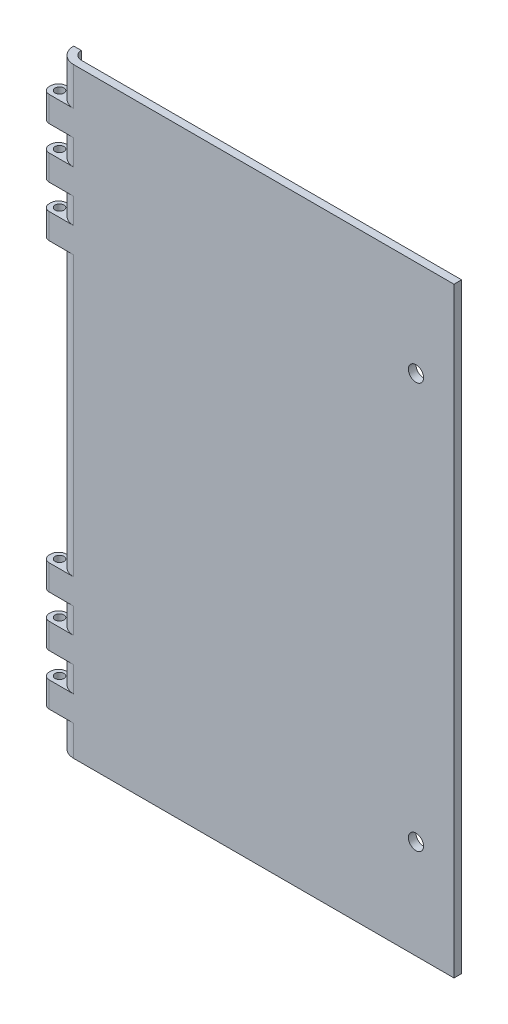
SolidWorks part; units mm, degrees
material "AISI 347 Annealed Stainless Steel (SS)"
ref_plane "Front Plane" through (0, 0, 0) normal (0, 0, 1) x (1, 0, 0)
ref_plane "Top Plane" through (0, 0, 0) normal (0, 1, 0) x (1, 0, 0)
ref_plane "Right Plane" through (0, 0, 0) normal (1, 0, 0) x (0, 0, -1)
sketch "Sketch1" plane through (0, 0, 0) normal (0, 1, 0) x (1, 0, 0)
  line L0 (0, 0) -> (381, 0)
  line L1 (397.1798, 16.1798) -> (397.1798, 244.7798)
  line L2 (190.5, 0) -> (190.5, 294.1102) construction
  line L3 (397.1798, 130.4798) -> (-232.7468, 130.4798) construction
  line L4 (0, 260.9596) -> (381, 260.9596)
  line L5 (-16.1798, 16.1798) -> (-16.1798, 244.7798)
  arc A0 (381, 0) -> (397.1798, 16.1798) centre (381, 16.1798) ccw
  arc A1 (381, 260.9596) -> (397.1798, 244.7798) centre (381, 244.7798) cw
  arc A2 (0, 0) -> (-16.1798, 16.1798) centre (0, 16.1798) cw
  arc A3 (0, 260.9596) -> (-16.1798, 244.7798) centre (0, 244.7798) ccw
  dimension "D2" = 16.1798
  dimension "D1" = 381
  dimension "D3" = 228.6
extrude "Boss-Extrude1" add sketch "Sketch1" against normal blind 609.6 contours L5 A3 L4 A1 L1 A0 L0 A2
shell "Shell1" thickness 7.62
sketch "Sketch3" plane through (0, 0, 0) normal (0, 1, 0) x (1, 0, 0)
  line L1 (381, 0) -> (409.862, 0)
  line L2 (381, 0) -> (381, 274.8146)
  line L3 (381, 274.8146) -> (409.862, 274.8146)
  line L4 (409.862, 0) -> (409.862, 274.8146)
extrude "Cut-Extrude2" cut sketch "Sketch3" against normal blind 609.6
sketch "Sketch4" plane through (0, 0, 0) normal (0, 1, 0) x (1, 0, 0)
  line L1 (-16.1798, 16.1798) -> (381, 16.1798)
  line L2 (-16.1798, 16.1798) -> (-16.1798, 260.9596)
  line L3 (-16.1798, 260.9596) -> (381, 260.9596)
  line L4 (381, 16.1798) -> (381, 260.9596)
extrude "Cut-Extrude3" cut sketch "Sketch4" against normal blind 609.6
sketch "Sketch5" plane through (0, 0, -16.1798) normal (0, 0, -1) x (-1, 0, 0)
  line L1 (16.1798, -609.6) -> (-381, -609.6)
  line L2 (16.1798, -609.6) -> (16.1798, -601.98)
  line L3 (16.1798, -601.98) -> (-381, -601.98)
  line L4 (-381, -609.6) -> (-381, -601.98)
extrude "Cut-Extrude4" cut sketch "Sketch5" against normal blind 609.6
ref_plane "Plane1" through (0, -63.5, 0) normal (0, 1, 0) x (1, 0, 0)
sketch "Sketch8" plane through (0, -63.5, 0) normal (0, 1, 0) x (1, 0, 0)
  line L0 (-16.1798, 16.1798) -> (-31.4198, 16.1798)
  line L1 (-31.4198, 16.1798) -> (-31.4198, 3.2512)
  line L2 (0, 0) -> (-28.1686, 0)
  line L7 (-8.5598, 16.1798) -> (-16.1798, 16.1798)
  line L8 (0, 0) -> (381, 0)
  line L9 (381, 0) -> (381, 7.62)
  line L10 (381, 7.62) -> (0, 7.62)
  arc A0 (-31.4198, 3.2512) -> (-28.1686, 0) centre (-28.1686, 3.2512) ccw
  arc A3 (-8.5598, 16.1798) -> (0, 7.62) centre (0, 16.1798) ccw
  arc A4 (-16.1798, 16.1798) -> (0, 0) centre (0, 16.1798) ccw
  arc A6 (-16.1798, 16.1798) -> (0, 0) centre (0, 16.1798) ccw
  dimension "D1" = 15.24
  dimension "D2" = 3.2512
  dimension "D3" = 0
extrude "Boss-Extrude4" add sketch "Sketch8" along normal blind 25.4
pattern_linear "LPattern2" count 3 spacing 50.8 along (0, -1, 0) of "Boss-Extrude4"
pattern_linear "LPattern3" count 2 spacing 508 along (0, -1, 0) of "Boss-Extrude4"
pattern_linear "LPattern6" count 2 spacing 457.2 along (0, -1, 0) of "Boss-Extrude4"
pattern_linear "LPattern7" count 2 spacing 406.4 along (0, -1, 0) of "Boss-Extrude4"
sketch "Sketch11" plane through (0, -63.5, 0) normal (0, 1, 0) x (1, 0, 0)
  line L0 (-16.1798, 16.1798) -> (-31.4198, 16.1798) construction
  line L1 (-31.4198, 16.1798) -> (-31.4198, 3.2512) construction
  circle A0 centre (-22.7838, 8.5598) radius 4.445
  dimension "D1" = 8.89
  dimension "D2" = 7.62
  dimension "D3" = 8.636
extrude "Cut-Extrude5" cut sketch "Sketch11" against normal through all both and the other way through all
sketch "Sketch13" plane through (0, 0, 0) normal (0, 0, 1) x (1, 0, 0)
  line L0 (0, -601.98) -> (0, -571.5)
sketch "Sketch14" plane through (0, -63.5, 0) normal (0, 1, 0) x (1, 0, 0)
  line L0 (-23.2902, 16.1798) -> (-23.2902, 22.3671)
  line L1 (-23.2902, 22.3671) -> (-43.4483, 22.3671)
  line L2 (-43.4483, 22.3671) -> (-43.4483, 8.0502)
  line L3 (-43.4483, 8.0502) -> (-31.4198, 8.0502)
  arc A0 (-23.2902, 16.1798) -> (-31.4198, 8.0502) centre (-23.2902, 8.0502) ccw
extrude "Cut-Extrude6" cut sketch "Sketch14" against normal through all both and the other way through all
sketch "Sketch15" plane through (0, -38.1, 0) normal (0, 1, 0) x (1, 0, 0)
  line L0 (-31.4198, 6.878) -> (-31.4198, 0)
  line L1 (-31.4198, 0) -> (-24.5418, 0)
  arc A0 (-31.4198, 6.878) -> (-24.5418, 0) centre (-24.5418, 6.878) ccw
extrude "Cut-Extrude7" cut sketch "Sketch15" against normal through all both and the other way through all
sketch "Sketch16" plane through (0, 0, 0) normal (0, 0, 1) x (1, 0, 0)
  line L0 (381, -601.98) -> (381, 0) construction
  line L1 (0, 0) -> (381, 0) construction
  circle A0 centre (342.9, -96.52) radius 7.62
  circle A1 centre (342.9, -502.92) radius 7.62
  dimension "D1" = 15.24
  dimension "D4" = 15.24
  dimension "D2" = 38.1
  dimension "D3" = 96.52
  dimension "D5" = 38.1
  dimension "D6" = 406.4
extrude "Cut-Extrude8" cut sketch "Sketch16" against normal through all both and the other way through all
